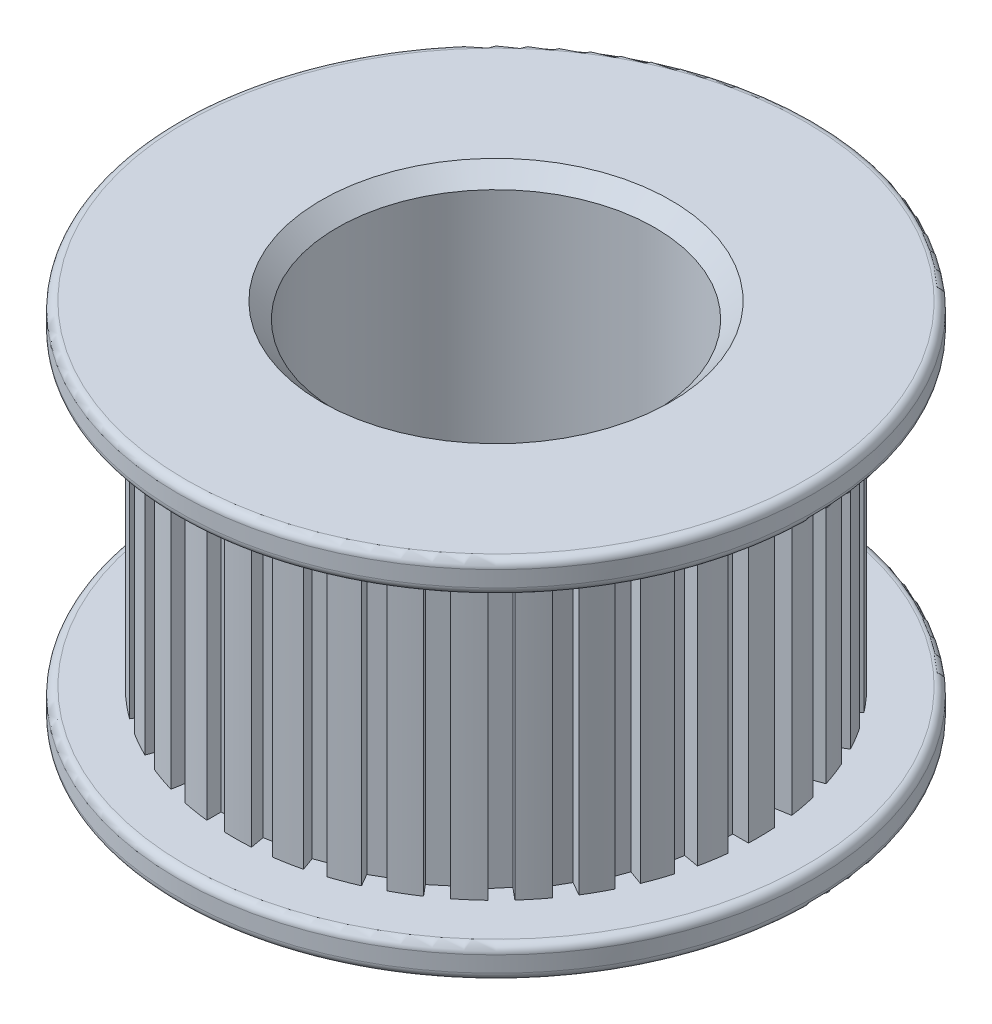
SolidWorks part; units mm, degrees
ref_plane "Front Plane" through (0, 0, 0) normal (0, 0, 1) x (1, 0, 0)
ref_plane "Top Plane" through (0, 0, 0) normal (0, 1, 0) x (1, 0, 0)
ref_plane "Right Plane" through (0, 0, 0) normal (1, 0, 0) x (0, 0, -1)
sketch "Sketch1" plane through (0, 0, 0) normal (0, 0, 1) x (1, 0, 0)
  line L0 (254, 0) -> (508, 0)
  line L1 (508, 0) -> (508, 50.8)
  line L2 (508, 50.8) -> (419.1, 50.8)
  line L3 (419.1, 50.8) -> (419.1, 533.4)
  line L4 (419.1, 533.4) -> (508, 533.4)
  line L5 (508, 533.4) -> (508, 584.2)
  line L6 (508, 584.2) -> (254, 584.2)
  line L7 (254, 584.2) -> (254, 0)
  line L8 (0, 0) -> (0, 345.2148) construction
  dimension "D1" = 254
  dimension "D2" = 254
  dimension "D3" = 254
  dimension "D4" = 50.8
  dimension "D5" = 50.8
  dimension "D6" = 584.2
  dimension "D7" = 88.9
revolve "Revolve1" add sketch "Sketch1" angle 360 about L8
chamfer "Chamfer1" distance 25.4 angle 45 1 edges at (0, 584.2, -254)
fillet "Fillet1" radius 12.7 4 edges at (0, 584.2, -508) (0, 533.4, -508) (0, 0, -508) (0, 50.8, -508)
sketch "Sketch3" plane through (0, 50.8, 0) normal (0, 1, 0) x (1, 0, 0)
  line L1 (15.24, 393.7) -> (45.72, 393.7)
  line L2 (15.24, 393.7) -> (15.24, 424.18)
  line L3 (15.24, 424.18) -> (45.72, 424.18)
  line L4 (45.72, 393.7) -> (45.72, 424.18)
  line L5 (15.24, 393.7) -> (45.72, 424.18) construction
  line L6 (15.24, 424.18) -> (45.72, 393.7) construction
  point P0 (30.48, 408.94)
  dimension "D1" = 30.48
  dimension "D2" = 30.48
  dimension "D3" = 393.7
  dimension "D4" = 15.24
extrude "Cut-Extrude1" cut sketch "Sketch3" along normal up to surface (482.6 mm away) up to face at (0, 533.4, -495.3)
pattern_circular "CirPattern1" count 36 every 10 about axis through (0, 0, 0) along (0, 1, 0) of "Cut-Extrude1"
fillet "Fillet2" radius 12.7 1 edges at (0, 0, -254)
